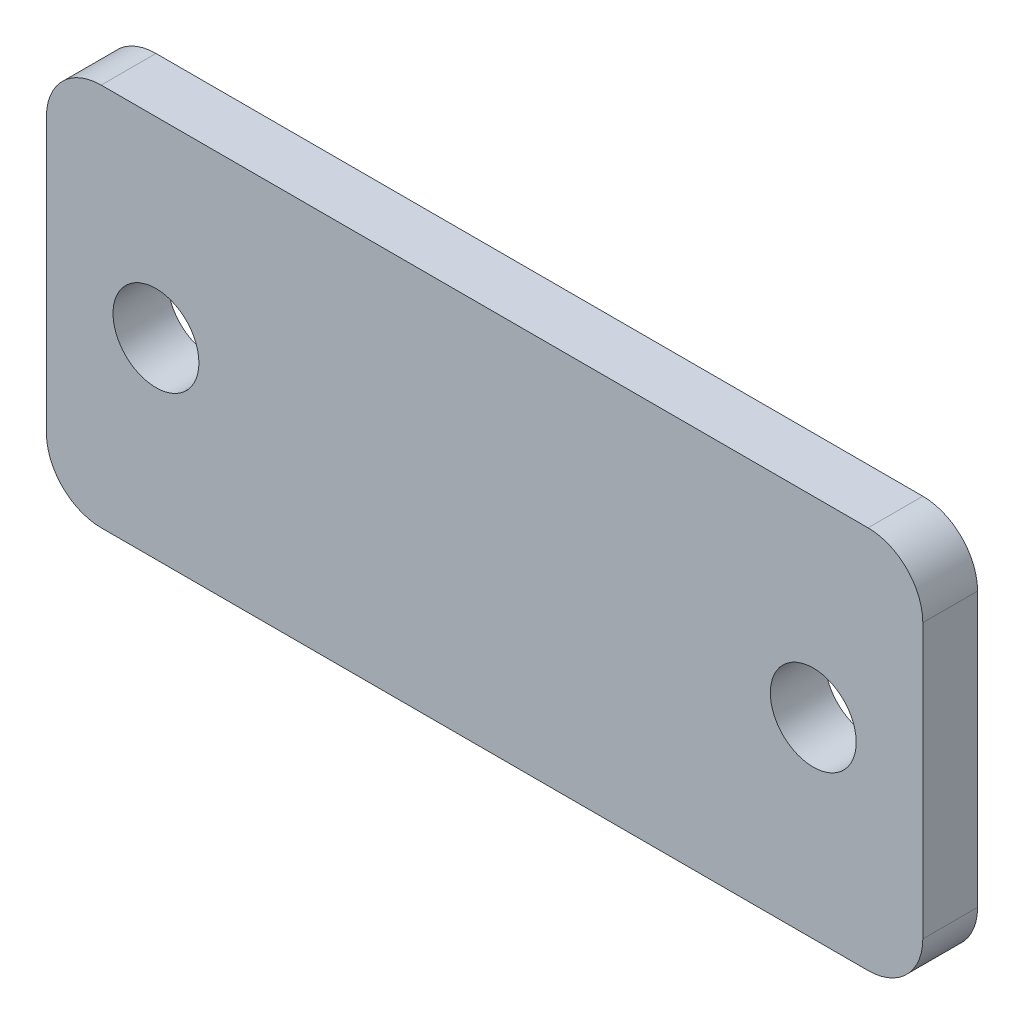
SolidWorks part; units mm, degrees
ref_plane "Front Plane" through (0, 0, 0) normal (0, 0, 1) x (1, 0, 0)
ref_plane "Top Plane" through (0, 0, 0) normal (0, 1, 0) x (1, 0, 0)
ref_plane "Right Plane" through (0, 0, 0) normal (1, 0, 0) x (0, 0, -1)
sketch "Sketch1" plane through (0, 0, 0) normal (0, 0, 1) x (1, 0, 0)
  line L0 (-19.05, 0) -> (19.05, 0) construction
  line L1 (-25.4, -11.1125) -> (25.4, -11.1125)
  line L2 (-25.4, -11.1125) -> (-25.4, 11.1125)
  line L3 (-25.4, 11.1125) -> (25.4, 11.1125)
  line L4 (25.4, -11.1125) -> (25.4, 11.1125)
  circle A0 centre (-19.05, 0) radius 2.4892
  circle A1 centre (19.05, 0) radius 2.4892
  point P5 (-25.4, 0)
  point P6 (0, 11.1125)
  point P11 (0, 0)
  point P12 (0, 0)
  point P13 (0, 0)
  dimension "D3" = 4.9784
  dimension "D1" = 50.8
  dimension "D2" = 22.225
  dimension "D4" = 38.1
extrude "Boss-Extrude1" add sketch "Sketch1" along normal blind 3.175
fillet "Fillet1" radius 3.175 4 edges at (-25.4, 11.1125, 1.5875) (25.4, -11.1125, 1.5875) (-25.4, -11.1125, 1.5875) (25.4, 11.1125, 1.5875)
equation "\"0.125n\"=0.1"
